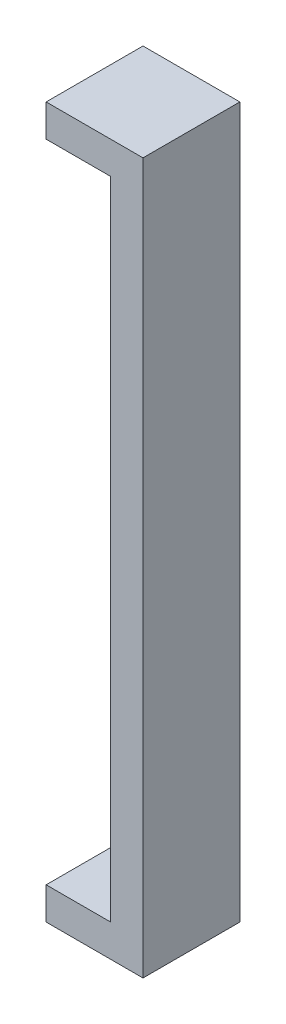
SolidWorks part; units mm, degrees
ref_plane "Alzado" through (0, 0, 0) normal (0, 0, 1) x (1, 0, 0)
ref_plane "Planta" through (0, 0, 0) normal (0, 1, 0) x (1, 0, 0)
ref_plane "Vista lateral" through (0, 0, 0) normal (1, 0, 0) x (0, 0, -1)
sketch "Croquis1" plane through (0, 0, 0) normal (0, 1, 0) x (1, 0, 0)
  line L0 (-3.06, 6.21) -> (5.94, 6.21)
  line L1 (5.94, 6.21) -> (5.94, -2.79)
  line L2 (5.94, -2.79) -> (2.94, -2.79)
  line L3 (2.94, -2.79) -> (2.94, 3.21)
  line L4 (2.94, 3.21) -> (-3.06, 3.21)
  line L5 (-3.06, 6.21) -> (-3.06, 3.21)
  dimension "D1" = 3
  dimension "D2" = 3
  dimension "D3" = 6
  dimension "D4" = 6
extrude "Saliente-Extruir1" add sketch "Croquis1" along normal mid plane 66
sketch "Croquis2" plane through (0, 0, -3.21) normal (0, 0, 1) x (1, 0, 0)
  line L0 (2.94, 33) -> (2.94, -33) construction
  line L1 (-3.06, 33) -> (2.94, 33)
  line L2 (-3.06, 33) -> (-3.06, 30)
  line L3 (-3.06, 30) -> (2.94, 30)
  line L4 (2.94, 33) -> (2.94, 30)
  dimension "D1" = 3
extrude "Saliente-Extruir2" add sketch "Croquis2" along normal through all
mirror "Simetría1" about plane through (0, 0, 0) normal (0, 1, 0) of "Saliente-Extruir2"
